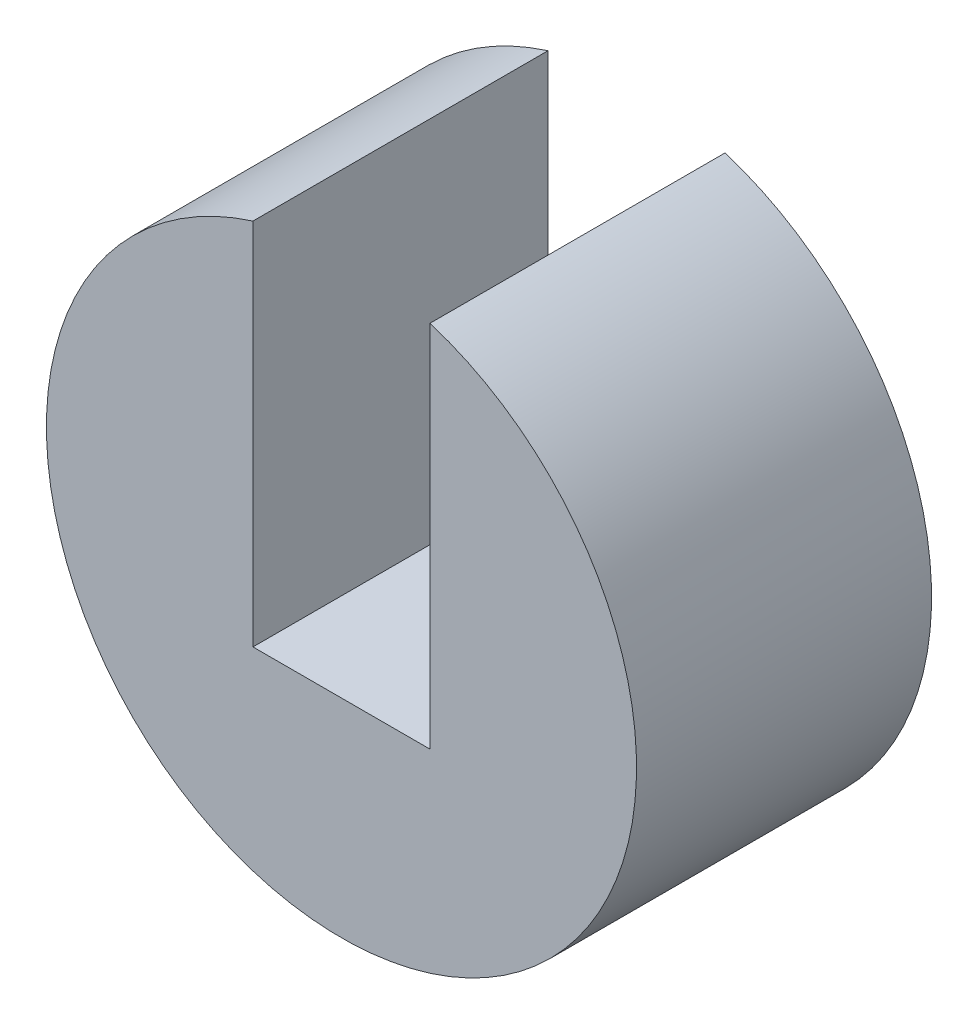
SolidWorks part; units mm, degrees
ref_plane "Front Plane" through (0, 0, 0) normal (0, 0, 1) x (1, 0, 0)
ref_plane "Top Plane" through (0, 0, 0) normal (0, 1, 0) x (1, 0, 0)
ref_plane "Right Plane" through (0, 0, 0) normal (1, 0, 0) x (0, 0, -1)
sketch "Sketch1" plane through (0, 0, 0) normal (0, 0, 1) x (1, 0, 0)
  line L1 (1.5, -3.125) -> (-1.5, -3.125)
  line L2 (1.5, -3.125) -> (1.5, 3.125)
  line L3 (1.5, 3.125) -> (-1.5, 3.125)
  line L4 (-1.5, -3.125) -> (-1.5, 3.125)
  line L5 (1.5, -3.125) -> (-1.5, 3.125) construction
  line L6 (1.5, 3.125) -> (-1.5, -3.125) construction
  circle A0 centre (0, -1.6447) radius 5
  point P0 (0, 0)
  point P8 (0, 0)
  dimension "D3" = 10
  dimension "D1" = 3
  dimension "D2" = 6.25
extrude "Boss-Extrude1" add sketch "Sketch1" along normal blind 5 contours L4 A0 L2 L1
